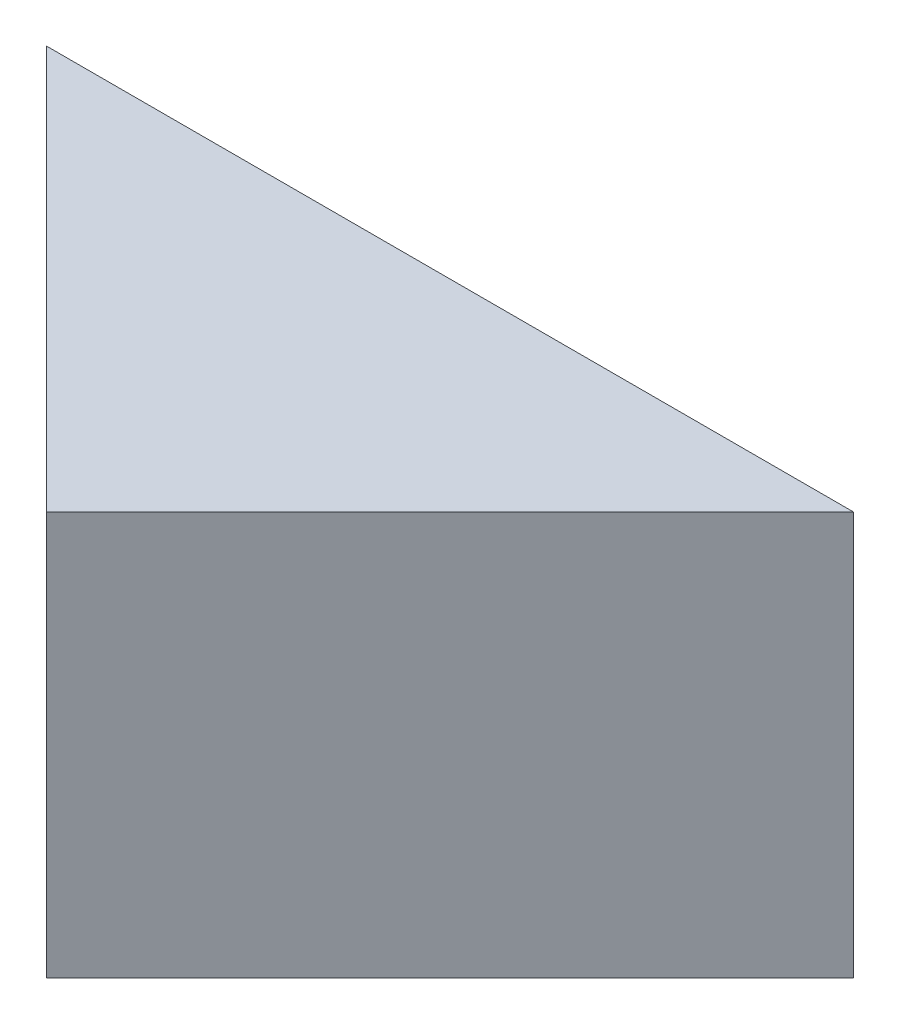
SolidWorks part; units mm, degrees
ref_plane "Přední rovina" through (0, 0, 0) normal (0, 0, 1) x (1, 0, 0)
ref_plane "Horní rovina" through (0, 0, 0) normal (0, 1, 0) x (1, 0, 0)
ref_plane "Pravá rovina" through (0, 0, 0) normal (1, 0, 0) x (0, 0, -1)
sketch "Sketch1" plane through (0, 0, 0) normal (0, 1, 0) x (1, 0, 0)
  line L0 (-20, 0) -> (20, 0)
  line L1 (20, 0) -> (0, -20)
  line L2 (0, -20) -> (0, 0) construction
  line L3 (-20, 0) -> (0, -20)
  dimension "D1" = 45
  dimension "D2" = 20
extrude "Boss-Extrude1" add sketch "Sketch1" along normal blind 20
